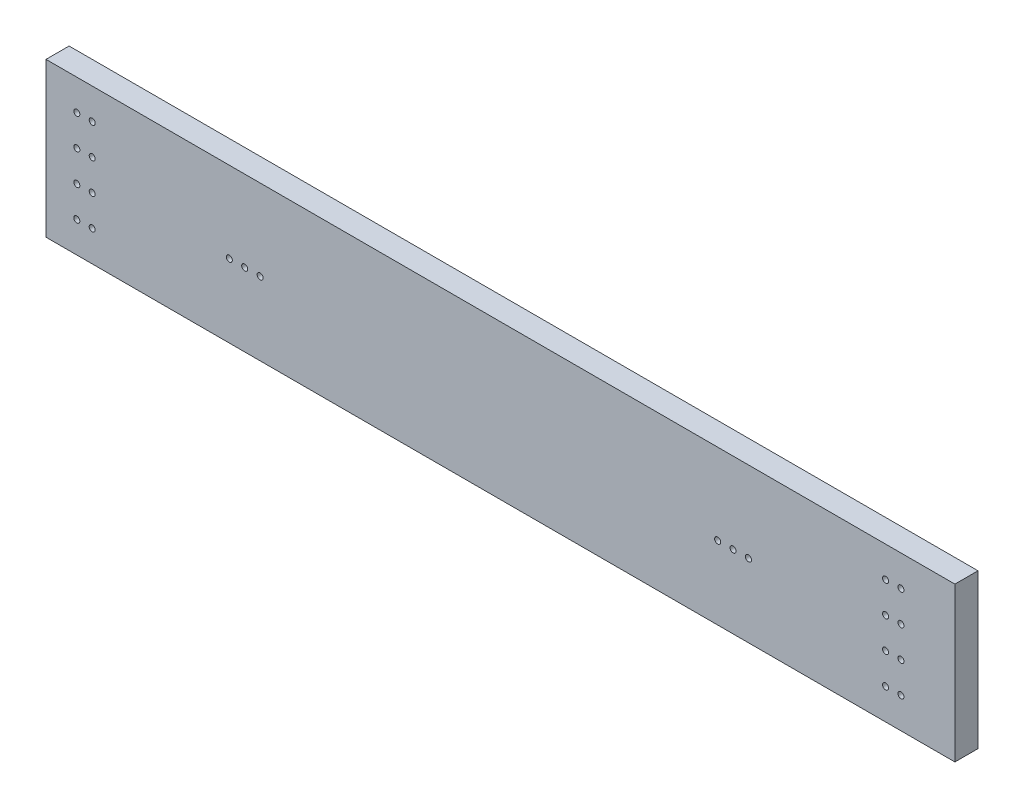
SolidWorks part; units mm, degrees
material "Pine"
ref_plane "Front Plane" through (0, 0, 0) normal (0, 0, 1) x (1, 0, 0)
ref_plane "Top Plane" through (0, 0, 0) normal (0, 1, 0) x (1, 0, 0)
ref_plane "Right Plane" through (0, 0, 0) normal (1, 0, 0) x (0, 0, -1)
sketch "Sketch1" plane through (0, 0, 0) normal (0, 0, 1) x (1, 0, 0)
  line L0 (361.95, 127) -> (361.95, 0) construction
  line L1 (0, 0) -> (749.3, 0)
  line L2 (0, 0) -> (0, 127)
  line L3 (0, 127) -> (749.3, 127)
  line L4 (749.3, 0) -> (749.3, 127)
  line L5 (19.05, 127) -> (19.05, 0) construction
  line L6 (25.4, 127) -> (25.4, 0) construction
  line L8 (730.25, 127) -> (730.25, 0) construction
  circle A0 centre (553.72, 60.325) radius 2.4892
  circle A1 centre (176.53, 60.325) radius 2.4892
  circle A2 centre (163.83, 60.325) radius 2.4892
  circle A3 centre (566.42, 60.325) radius 2.4892
  circle A4 centre (579.12, 60.325) radius 2.4892
  circle A5 centre (151.13, 60.325) radius 2.4892
  circle A6 centre (25.4, 25.4) radius 2.4892
  circle A7 centre (38.1, 25.4) radius 2.4892
  circle A8 centre (38.1, 50.8) radius 2.4892
  circle A9 centre (38.1, 76.2) radius 2.4892
  circle A10 centre (38.1, 101.6) radius 2.4892
  circle A12 centre (25.4, 50.8) radius 2.4892
  circle A13 centre (25.4, 76.2) radius 2.4892
  circle A14 centre (25.4, 101.6) radius 2.4892
  circle A18 centre (692.15, 25.4) radius 2.4892
  circle A19 centre (704.85, 25.4) radius 2.4892
  circle A20 centre (704.85, 50.8) radius 2.4892
  circle A21 centre (704.85, 76.2) radius 2.4892
  circle A22 centre (704.85, 101.6) radius 2.4892
  circle A24 centre (692.15, 50.8) radius 2.4892
  circle A25 centre (692.15, 76.2) radius 2.4892
  circle A26 centre (692.15, 101.6) radius 2.4892
  point P15 (361.95, 60.325)
  dimension "D6" = 4.9784
  dimension "D8" = 185.42
  dimension "D10" = 12.7
  dimension "D11" = 12.7
  dimension "D12" = 12.7
  dimension "D13" = 12.7
  dimension "D16" = 12.7
  dimension "D17" = 25.4
  dimension "D18" = 25.4
  dimension "D19" = 25.4
  dimension "D22" = 25.4
  dimension "D23" = 12.7
  dimension "D24" = 25.4
  dimension "D25" = 4.9784
  dimension "D7" = 191.77
  dimension "D27" = 60.325
  dimension "D1" = 127
  dimension "D2" = 749.3
  dimension "D3" = 336.55
  dimension "D4" = 19.05
  dimension "D5" = 6.35
  dimension "D9" = 19.05
  dimension "D26" = 44.45
  dimension "D14" = 2
  dimension "D15" = 4
  dimension "D20" = 2
  dimension "D21" = 4
extrude "Boss-Extrude1" add sketch "Sketch1" along normal mid plane 19.05
